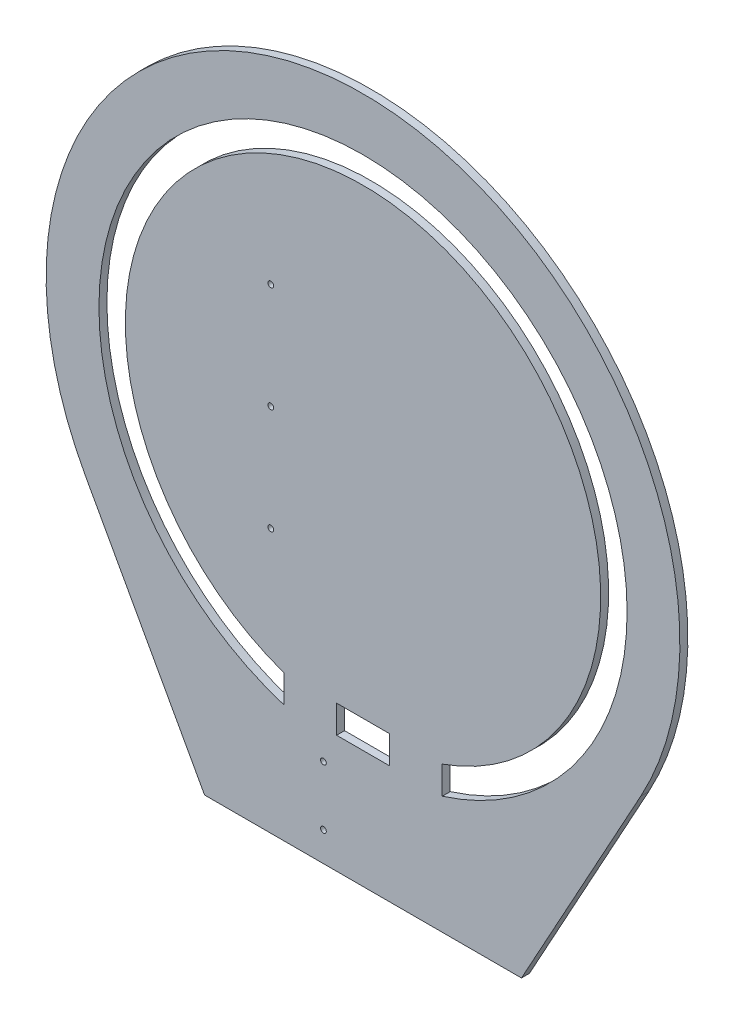
SolidWorks part; units mm, degrees
ref_plane "Plano frontal" through (0, 0, 0) normal (0, 0, 1) x (1, 0, 0)
ref_plane "Plano superior" through (0, 0, 0) normal (0, 1, 0) x (1, 0, 0)
ref_plane "Plano direito" through (0, 0, 0) normal (1, 0, 0) x (0, 0, -1)
sketch "Sketch1" plane through (0, 0, 0) normal (0, 0, 1) x (1, 0, 0)
  line L0 (-15, -35) -> (-7.5, -35)
  line L1 (-15, -35) -> (15, -35)
  line L4 (-15, -35) -> (-7.5, -35)
  line L5 (-7.5, -35) -> (-7.5, -23.8485)
  line L6 (-2.5, -23.8485) -> (2.5, -23.8485)
  line L7 (15, -35) -> (26.2929, -14.4459)
  line L8 (-2.5, -23.8485) -> (-2.5, -22.3607)
  line L9 (-7.5, -23.8485) -> (-7.5, -21.2132)
  line L10 (-2.5, -23.8485) -> (2.5, -23.8485)
  line L11 (2.5, -23.8485) -> (2.5, -22.3607)
  line L12 (7.5, -23.8485) -> (7.5, -21.2132)
  line L13 (2.5, -21.2132) -> (-2.5, -21.2132)
  line L14 (-2.5, -22.3607) -> (-2.5, -21.2132)
  line L15 (2.5, -22.3607) -> (2.5, -21.2132)
  line L16 (-15, -35) -> (-26.2929, -14.4459)
  arc A0 (7.5, -21.2132) -> (-7.5, -21.2132) centre (0, 0) ccw
  arc A1 (7.5, -23.8485) -> (-7.5, -23.8485) centre (0, 0) ccw
  arc A2 (26.2929, -14.4459) -> (-26.2929, -14.4459) centre (0, 0) ccw
  circle A3 centre (-3.75, -26.6242) radius 0.2718
  circle A4 centre (-3.75, -32.2242) radius 0.2718
  circle A5 centre (-8.7338, -10) radius 0.2718
  circle A6 centre (-8.7338, 0) radius 0.2718
  circle A7 centre (-8.7338, 10) radius 0.2718
  point P10 (0, -35)
  dimension "D1" = 45
  dimension "D2" = 50
  dimension "D3" = 60
  dimension "D4" = 5
  dimension "D5" = 30
  dimension "D6" = 7.5
  dimension "D7" = 5
  dimension "D8" = 2.6353
extrude "Boss-Extrude1" add sketch "Sketch1" along normal blind 0.7544
